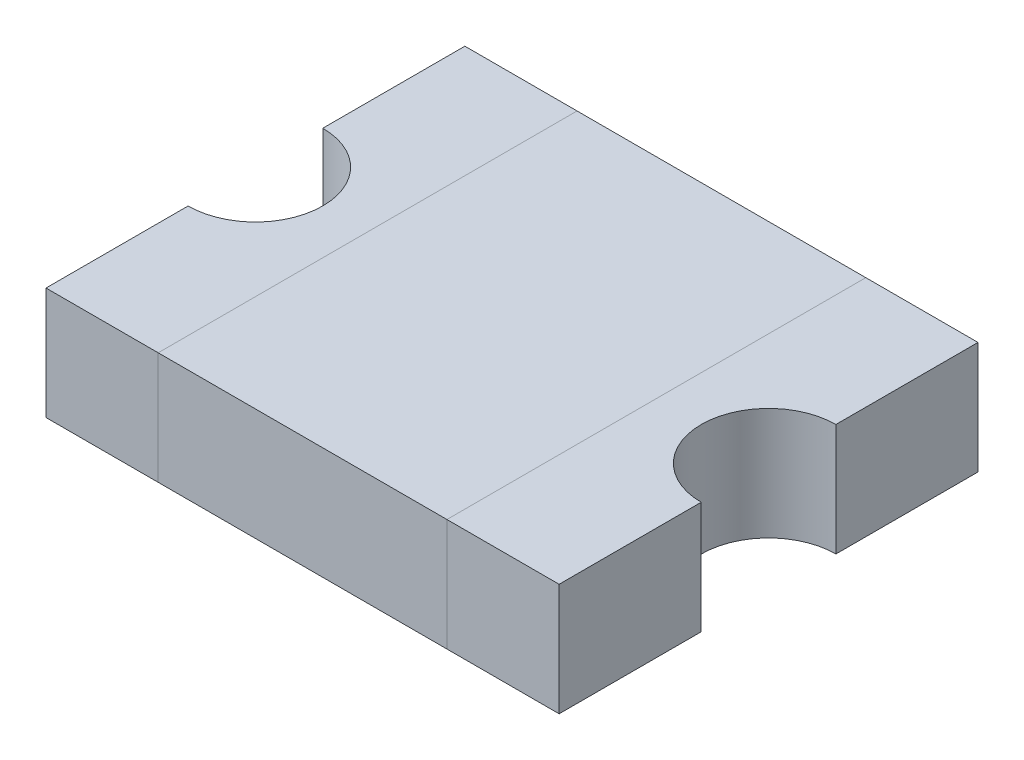
SolidWorks part; units mm, degrees
ref_plane "Front Plane" through (0, 0, 0) normal (0, 0, 1) x (1, 0, 0)
ref_plane "Top Plane" through (0, 0, 0) normal (0, 1, 0) x (1, 0, 0)
ref_plane "Right Plane" through (0, 0, 0) normal (1, 0, 0) x (0, 0, -1)
sketch "Sketch1" plane through (0, 0, 0) normal (0, 1, 0) x (1, 0, 0)
  line L1 (-0.965, -1.4) -> (0.965, -1.4)
  line L2 (-0.965, -1.4) -> (-0.965, 1.4)
  line L3 (-0.965, 1.4) -> (0.965, 1.4)
  line L4 (0.965, -1.4) -> (0.965, 1.4)
  line L5 (-0.965, -1.4) -> (0.965, 1.4) construction
  line L6 (-0.965, 1.4) -> (0.965, -1.4) construction
  point P0 (0, 0)
  dimension "D1" = 2.8
  dimension "D2" = 1.93
extrude "Boss-Extrude1" add sketch "Sketch1" along normal blind 0.75
sketch "Sketch2" plane through (0, 0, 0) normal (0, 1, 0) x (1, 0, 0)
  line L0 (1.715, -0.45) -> (1.715, -1.4)
  line L1 (1.715, 1.4) -> (1.715, 0.45)
  line L2 (0.965, -1.4) -> (1.715, -1.4)
  line L3 (0.965, 1.4) -> (1.715, 1.4)
  line L4 (-0.965, 1.4) -> (-0.965, -1.4)
  line L5 (-0.965, 1.4) -> (-1.715, 1.4)
  line L6 (-0.965, -1.4) -> (-1.715, -1.4)
  line L7 (-1.715, 1.4) -> (-1.715, 0.45)
  line L8 (-1.715, -0.45) -> (-1.715, -1.4)
  line L9 (0, 1.4) -> (0, -1.4) construction
  line L10 (0.965, 1.4) -> (-0.965, 1.4) construction
  line L11 (-0.965, -1.4) -> (0.965, -1.4) construction
  line L12 (0.965, 1.4) -> (0.965, -1.4)
  arc A0 (-1.715, 0.45) -> (-1.715, -0.45) centre (-1.715, 0) cw
  arc A1 (1.715, 0.45) -> (1.715, -0.45) centre (1.715, 0) ccw
  dimension "D1" = 0.75
extrude "Boss-Extrude3" add sketch "Sketch2" along normal blind 0.75 separate body
